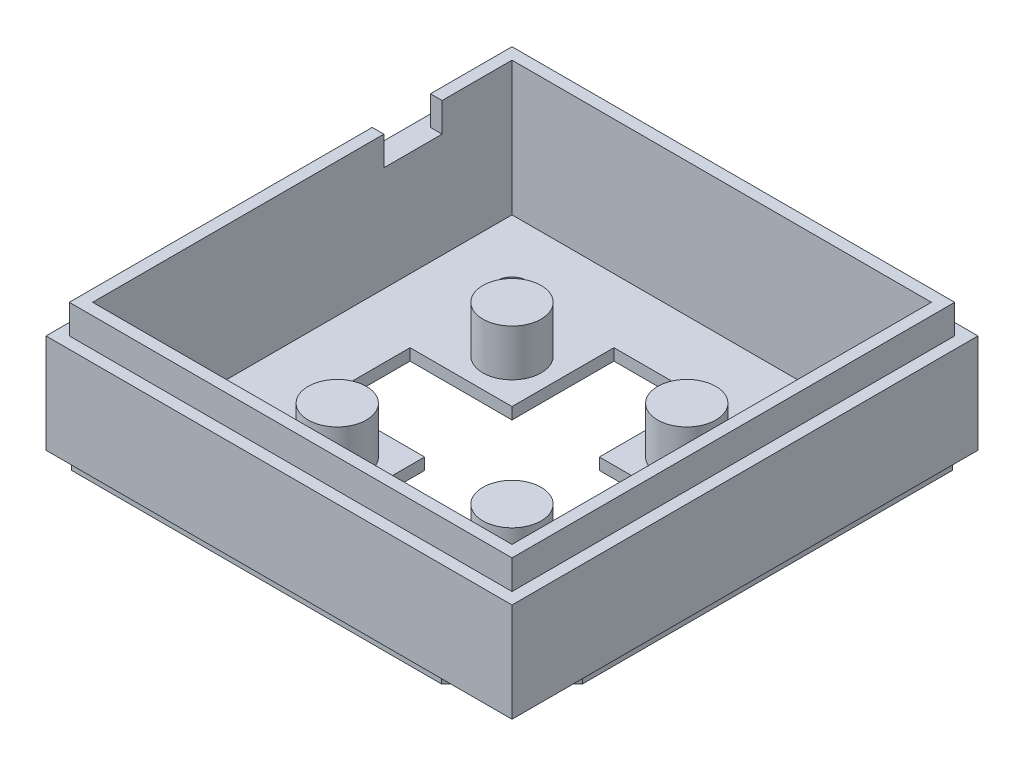
SolidWorks part; units mm, degrees
ref_plane "Plan de face" through (0, 0, 0) normal (0, 0, 1) x (1, 0, 0)
ref_plane "Plan de dessus" through (0, 0, 0) normal (0, 1, 0) x (1, 0, 0)
ref_plane "Plan de droite" through (0, 0, 0) normal (1, 0, 0) x (0, 0, -1)
sketch "Esquisse1" plane through (0, 0, 0) normal (0, 1, 0) x (1, 0, 0)
  line L1 (0, 0) -> (80, 0)
  line L2 (0, 0) -> (0, -80)
  line L3 (0, -80) -> (80, -80)
  line L4 (80, 0) -> (80, -80)
  dimension "D1" = 80
  dimension "D2" = 80
extrude "Boss.-Extru.1" add sketch "Esquisse1" along normal blind 20
sketch "Esquisse2" plane through (0, 20, 0) normal (0, 1, 0) x (1, 0, 0)
  line L1 (78, -2) -> (2, -2)
  line L2 (78, -2) -> (78, -78)
  line L3 (78, -78) -> (2, -78)
  line L4 (2, -2) -> (2, -78)
  line L5 (78, -2) -> (2, -78) construction
  line L6 (78, -78) -> (2, -2) construction
  point P0 (40, -40)
  dimension "D1" = 76
  dimension "D2" = 76
extrude "Boss.-Extru.2" add sketch "Esquisse2" along normal blind 5
sketch "Esquisse3" plane through (0, 25, 0) normal (0, 1, 0) x (1, 0, 0)
  line L1 (4, -4) -> (76, -4)
  line L2 (4, -4) -> (4, -76)
  line L3 (4, -76) -> (76, -76)
  line L4 (76, -4) -> (76, -76)
  line L5 (4, -4) -> (76, -76) construction
  line L6 (4, -76) -> (76, -4) construction
  point P0 (40, -40)
  dimension "D1" = 72
  dimension "D2" = 72
extrude "Enlèv. mat.-Extru.2" cut sketch "Esquisse3" against normal blind 23
sketch "Esquisse4" plane through (0, 0, 0) normal (0, -1, 0) x (1, 0, 0)
  line L1 (47.5, 15) -> (32.5, 15)
  line L2 (47.5, 15) -> (47.5, 65)
  line L3 (47.5, 65) -> (32.5, 65)
  line L4 (32.5, 15) -> (32.5, 65)
  line L5 (47.5, 15) -> (32.5, 65) construction
  line L6 (47.5, 65) -> (32.5, 15) construction
  line L7 (65, 47.5) -> (15, 47.5)
  line L8 (65, 47.5) -> (65, 32.5)
  line L9 (65, 32.5) -> (15, 32.5)
  line L10 (15, 47.5) -> (15, 32.5)
  line L11 (65, 47.5) -> (15, 32.5) construction
  line L12 (65, 32.5) -> (15, 47.5) construction
  point P0 (40, 40)
  point P5 (40, 40)
  point P6 (40, 40)
  dimension "D1" = 15
  dimension "D2" = 50
extrude "Enlèv. mat.-Extru.9" cut sketch "Esquisse4" against normal blind 10 contours L2 L9 L4 L1 | L7 L10 L9 L4 | L9 L2 L7 L4 | L9 L8 L7 L2 | L7 L2 L3 L4
sketch "Esquisse7" plane through (0, 0, 0) normal (0, -1, 0) x (-1, 0, 0)
  line L0 (0, 0) -> (0, -80) construction
  line L1 (-80, -80) -> (-80, 0) construction
  line L2 (0, -80) -> (-80, -80) construction
  line L3 (-80, 0) -> (0, 0) construction
  circle A0 centre (-15, -15) radius 2.5
  circle A1 centre (-15, -65) radius 2.5
  circle A2 centre (-65, -15) radius 2.5
  circle A3 centre (-65, -65) radius 2.5
  dimension "D1" = 5
  dimension "D2" = 5
  dimension "D3" = 5
  dimension "D4" = 5
  dimension "D5" = 15
  dimension "D6" = 15
  dimension "D7" = 15
  dimension "D8" = 15
  dimension "D9" = 15
  dimension "D10" = 15
  dimension "D11" = 15
  dimension "D12" = 15
extrude "Enlèv. mat.-Extru.4" cut sketch "Esquisse7" against normal blind 10
sketch "Esquisse5" plane through (0, 0, 0) normal (0, -1, 0) x (-1, 0, 0)
  line L0 (-80, 0) -> (0, 0) construction
  line L1 (0, 0) -> (0, -80) construction
  circle A0 centre (-55, -25) radius 5
  circle A1 centre (-55, -55) radius 5
  circle A2 centre (-25, -55) radius 5
  circle A3 centre (-25, -25) radius 5
  dimension "D3" = 10
  dimension "D4" = 10
  dimension "D5" = 10
  dimension "D6" = 10
  dimension "D1" = 30
  dimension "D2" = 25
  dimension "D7" = 25
  dimension "D8" = 30
sketch "Esquisse9" plane through (0, 0, 0) normal (0, -1, 0) x (-1, 0, 0)
  line L0 (-80, 0) -> (0, 0) construction
  line L1 (0, 0) -> (0, -80) construction
  circle A0 centre (-55, -25) radius 2
  circle A1 centre (-55, -55) radius 2
  circle A2 centre (-25, -25) radius 2
  circle A3 centre (-25, -55) radius 2
  dimension "D1" = 4
  dimension "D2" = 4
  dimension "D3" = 4
  dimension "D4" = 4
  dimension "D5" = 30
  dimension "D6" = 25
  dimension "D7" = 25
  dimension "D8" = 30
extrude "Boss.-Extru.6" add sketch "Esquisse5" against normal blind 10 contours A0 | A1 | A2 | A3
extrude "Enlèv. mat.-Extru.6" cut sketch "Esquisse9" against normal blind 8
sketch "Esquisse10" plane through (0, 25, 0) normal (0, 1, 0) x (1, 0, 0)
  line L1 (2, -16) -> (4, -16)
  line L2 (2, -16) -> (2, -26)
  line L3 (2, -26) -> (4, -26)
  line L4 (4, -16) -> (4, -26)
  line L5 (4, -4) -> (4, -76) construction
  dimension "D1" = 10
extrude "Enlèv. mat.-Extru.7" cut sketch "Esquisse10" against normal blind 5
sketch "Esquisse11" plane through (0, 0, 0) normal (0, -1, 0) x (-1, 0, 0)
  line L0 (-80, 0) -> (0, 0) construction
  line L1 (-2.2, -77.8) -> (-77.8, -77.8)
  line L2 (-2.2, -77.8) -> (-2.2, -2.2)
  line L3 (-2.2, -2.2) -> (-77.8, -2.2)
  line L4 (-77.8, -77.8) -> (-77.8, -2.2)
  line L5 (0, 0) -> (0, -80) construction
  line L6 (0, -80) -> (-80, -80) construction
  line L7 (-80, -80) -> (-80, 0) construction
  dimension "D1" = 2.2
  dimension "D2" = 2.2
  dimension "D3" = 2.2
  dimension "D4" = 2.2
  dimension "D5" = 75.6
  dimension "D6" = 75.6
extrude "Enlèv. mat.-Extru.10" cut sketch "Esquisse11" against normal blind 3 flip side to cut
sketch "Esquisse14" plane through (0, 20, 0) normal (0, 1, 0) x (1, 0, 0)
  line L0 (76, -76) -> (76, -65.7031)
  line L1 (76, -76) -> (76, -4) construction
  line L2 (76, -65.7031) -> (66.7033, -76)
  line L3 (4, -76) -> (76, -76) construction
  line L4 (66.7033, -76) -> (76, -76)
extrude "Boss.-Extru.7" add sketch "Esquisse14" against normal up to next from offset 15 offset against normal yes
sketch "Esquisse13" plane through (0, 0, 0) normal (0, -1, 0) x (-1, 0, 0)
  line L0 (-63.5, -80) -> (-80, -63.5)
  line L1 (-80, -80) -> (0, -80) construction
  line L2 (-80, 0) -> (-80, -80) construction
  line L3 (-80, -63.5) -> (-80, -80)
  line L4 (-80, -80) -> (-63.5, -80)
  line L5 (0, 0) -> (-80, 0) construction
  dimension "D1" = 63.5
  dimension "D2" = 63.5
extrude "Enlèv. mat.-Extru.11" cut sketch "Esquisse13" against normal blind 3
